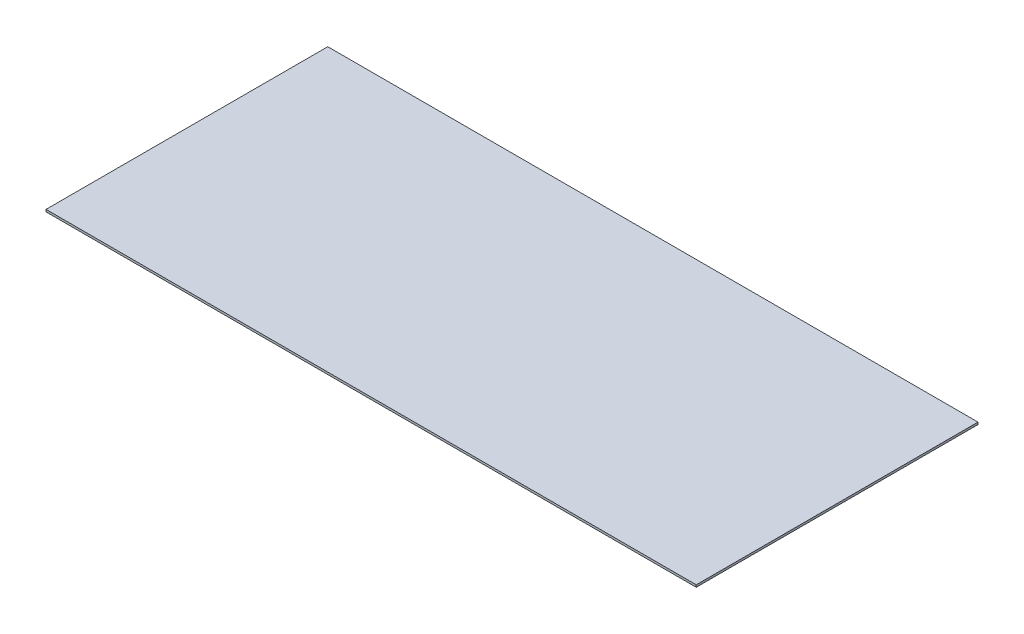
SolidWorks part; units mm, degrees
material "C355.0-T61 Многократное фасонное литье (SS)"
ref_plane "Спереди XY" through (0, 0, 0) normal (0, 0, 1) x (1, 0, 0)
ref_plane "Сверху XZ" through (0, 0, 0) normal (0, 1, 0) x (1, 0, 0)
ref_plane "Справа ZY" through (0, 0, 0) normal (1, 0, 0) x (0, 0, -1)
sketch "Эскиз1" plane through (0, 0, 0) normal (0, 1, 0) x (1, 0, 0)
  line L1 (300, -125) -> (-300, -125)
  line L2 (300, -125) -> (300, 135)
  line L3 (300, 135) -> (-300, 135)
  line L4 (-300, -125) -> (-300, 135)
  dimension "D1" = 260
  dimension "D2" = 600
extrude "Бобышка-Вытянуть1" add sketch "Эскиз1" along normal blind 2
